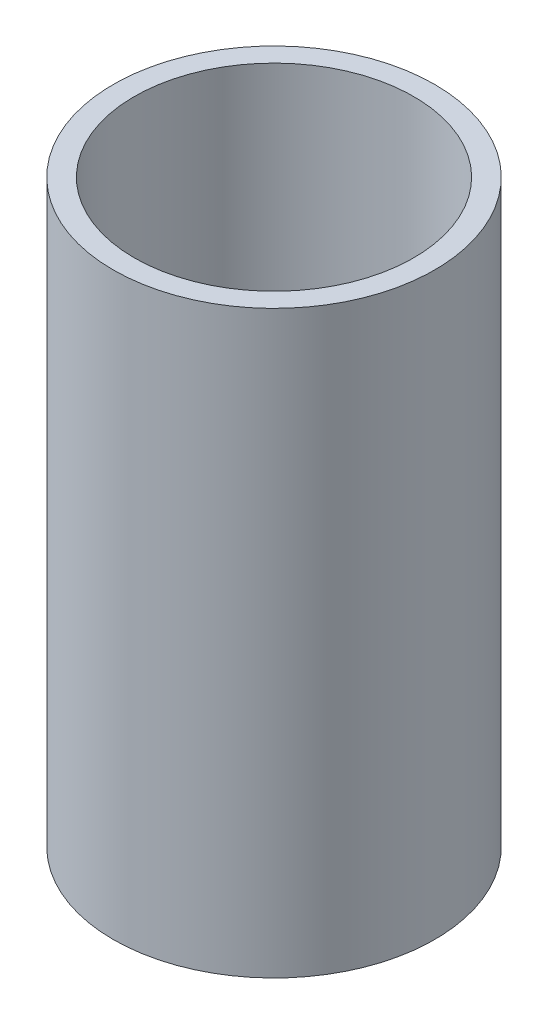
SolidWorks part; units mm, degrees
ref_plane "Front Plane" through (0, 0, 0) normal (0, 0, 1) x (1, 0, 0)
ref_plane "Top Plane" through (0, 0, 0) normal (0, 1, 0) x (1, 0, 0)
ref_plane "Right Plane" through (0, 0, 0) normal (1, 0, 0) x (0, 0, -1)
sketch "Sketch1" plane through (0, 0, 0) normal (0, 1, 0) x (1, 0, 0)
  circle A0 centre (0, 0) radius 10
  circle A1 centre (0, 0) radius 11.5
  dimension "D1" = 20
  dimension "D2" = 1.5
extrude "Boss-Extrude1" add sketch "Sketch1" along normal blind 40
sketch "Sketch2" plane through (0, 0, 0) normal (0, -1, 0) x (1, 0, 0)
  circle A0 centre (0, 0) radius 11.5 construction
  circle A1 centre (0, 0) radius 11.5
extrude "Boss-Extrude2" add sketch "Sketch2" along normal blind 1.5
